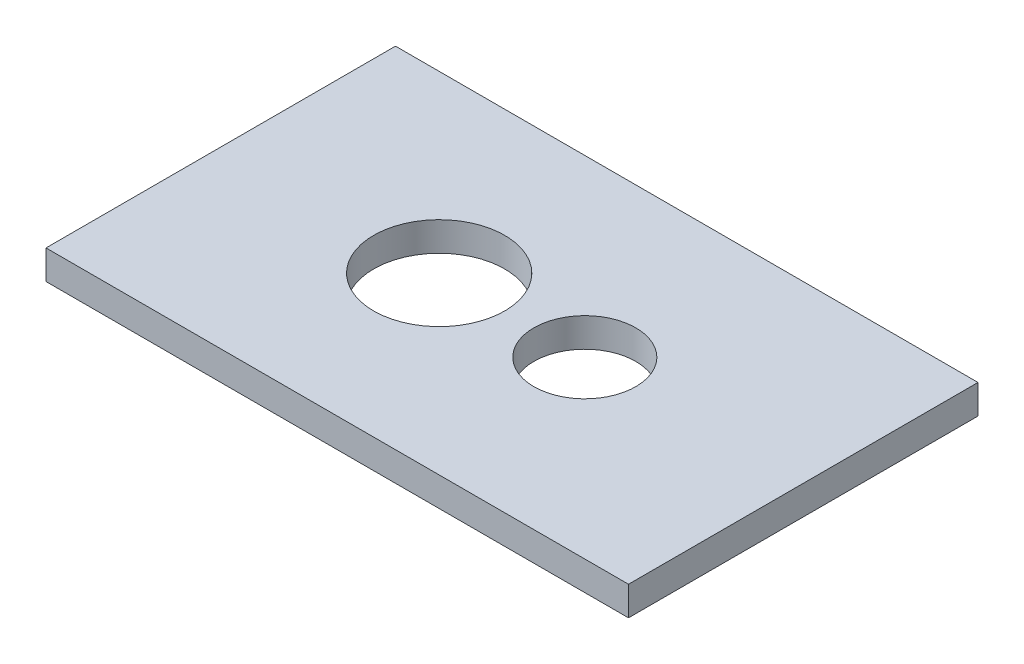
SolidWorks part; units mm, degrees
ref_plane "Front Plane" through (0, 0, 0) normal (0, 0, 1) x (1, 0, 0)
ref_plane "Top Plane" through (0, 0, 0) normal (0, 1, 0) x (1, 0, 0)
ref_plane "Right Plane" through (0, 0, 0) normal (1, 0, 0) x (0, 0, -1)
sketch "Sketch1" plane through (0, 0, 0) normal (0, 1, 0) x (1, 0, 0)
  line L1 (-63.5, -38.1) -> (63.5, -38.1)
  line L2 (-63.5, -38.1) -> (-63.5, 38.1)
  line L3 (-63.5, 38.1) -> (63.5, 38.1)
  line L4 (63.5, -38.1) -> (63.5, 38.1)
  line L5 (-63.5, -38.1) -> (63.5, 38.1) construction
  line L6 (-63.5, 38.1) -> (63.5, -38.1) construction
  point P0 (0, 0)
  dimension "D1" = 127
  dimension "D2" = 76.2
extrude "Boss-Extrude1" add sketch "Sketch1" along normal blind 6.35
sketch "Sketch2" plane through (0, 6.35, 0) normal (0, 1, 0) x (1, 0, 0)
  line L0 (-15.875, 0) -> (15.875, 0) construction
  circle A0 centre (-15.875, 0) radius 22.225 construction
  circle A1 centre (15.875, 0) radius 9.525 construction
  dimension "D1" = 44.45
  dimension "D2" = 19.05
sketch "Sketch3" plane through (0, 6.35, 0) normal (0, 1, 0) x (1, 0, 0)
  circle A0 centre (-15.875, 0) radius 14.2875
  dimension "D1" = 28.575
extrude "Cut-Extrude1" cut sketch "Sketch3" against normal through all
sketch "Sketch4" plane through (0, 6.35, 0) normal (0, 1, 0) x (1, 0, 0)
  circle A0 centre (15.875, 0) radius 11.1125
  dimension "D1" = 22.225
extrude "Cut-Extrude2" cut sketch "Sketch4" against normal through all
